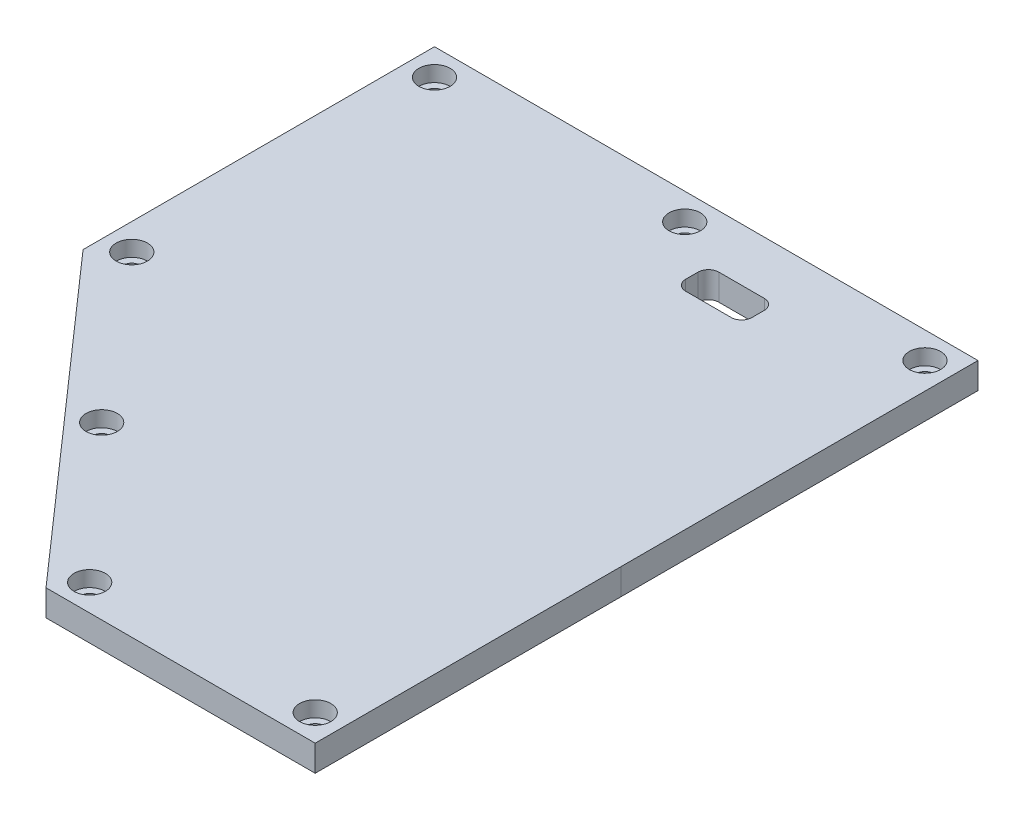
SolidWorks part; units mm, degrees
ref_plane "Front Plane" through (0, 0, 0) normal (0, 0, 1) x (1, 0, 0)
ref_plane "Top Plane" through (0, 0, 0) normal (0, 1, 0) x (1, 0, 0)
ref_plane "Right Plane" through (0, 0, 0) normal (1, 0, 0) x (0, 0, -1)
sketch "Sketch1" plane through (0, 0, 0) normal (0, 1, 0) x (1, 0, 0)
  line L0 (0, 0) -> (104.14, 0)
  line L2 (0, 0) -> (0, -67.34)
  line L4 (104.1401, -68.3797) -> (104.1401, -126.9997)
  line L5 (104.1401, -126.9997) -> (52.5601, -126.9997)
  line L6 (0, -67.34) -> (52.5601, -126.9997)
  line L11 (104.14, 0) -> (104.1401, -68.3797)
  dimension "D1" = 104.14
  dimension "D2" = 138.62
  dimension "D3" = 67.34
  dimension "D6" = 51.58
  dimension "D9" = 79.51
extrude "Boss-Extrude1" add sketch "Sketch1" along normal blind 5
sketch "Sketch2" plane through (0, 5, 0) normal (0, 1, 0) x (1, 0, 0)
  line L2 (104.1401, -126.9997) -> (104.1401, -68.3797) construction
  line L3 (52.5601, -126.9997) -> (104.1401, -126.9997) construction
  line L5 (104.14, 0) -> (0, 0) construction
  line L6 (0, 0) -> (0, -67.34) construction
  line L7 (0, -67.34) -> (52.5601, -126.9997) construction
  line L8 (104.1401, -68.3797) -> (104.14, 0) construction
  point P5 (99.0601, -121.9197)
  point P10 (55.8501, -121.9197)
  point P11 (99.06, -5.08)
  point P16 (5.08, -5.08)
  point P19 (53.03, -5.08)
  point P20 (5.08, -63.08)
  point P23 (30.4656, -94.2361)
  dimension "D2" = 5.08
  dimension "D3" = 5.08
  dimension "D4" = 5.08
  dimension "D5" = 43.21
  dimension "D6" = 5.08
  dimension "D8" = 5.08
  dimension "D9" = 5.08
  dimension "D10" = 5.08
  dimension "D11" = 47.95
  dimension "D12" = 58
  dimension "D13" = 5.08
  dimension "D14" = 37.56
  dimension "D15" = 5.08
hole_wizard "Ø4.0mm Dowel Hole1" positions "3DSketch1" profile "Sketch3" hole size "Ø4.0" standard "ANSI Metric"
sketch3d "3DSketch1"
  point P0 (5.08, 5, 5.08)
  point P3 (53.03, 5, 5.08)
  point P6 (99.06, 5, 5.08)
  point P12 (99.0601, 5, 121.9197)
  point P15 (55.8501, 5, 121.9197)
  point P18 (30.4656, 5, 94.2361)
  point P21 (5.08, 5, 63.08)
sketch "Sketch3" plane through (5.08, 5, 5.08) normal (1, 0, 0) x (0, 0, 1)
  line L0 (0, 0) -> (0, 5)
  line L1 (0, 5) -> (1.65, 5)
  line L2 (1.65, 5) -> (1.65, 0)
  line L5 (1.65, 0) -> (0, 0)
  line L10 (0, 5) -> (-1.65, 5) construction
  line L11 (0, -6.35) -> (0, 107.95) construction
  dimension "Hole Dia." = 3.3
  dimension "Hole Depth" = 5
  dimension "Drill Angle" = 180
sketch "Sketch4" plane through (0, 5, 0) normal (0, 1, 0) x (1, 0, 0)
  line L0 (104.14, 0) -> (0, 0) construction
  line L1 (0, 0) -> (0, -67.34) construction
  line L3 (62.65, -10.16) -> (75.35, -10.16)
  line L4 (62.65, -10.16) -> (62.65, -16.51)
  line L5 (62.65, -16.51) -> (75.35, -16.51)
  line L6 (75.35, -10.16) -> (75.35, -16.51)
  line L7 (62.65, -10.16) -> (75.35, -16.51) construction
  line L8 (62.65, -16.51) -> (75.35, -10.16) construction
  point P0 (69, -13.335)
  point P5 (69, -13.335)
  dimension "D1" = 13.335
  dimension "D2" = 69
  dimension "D3" = 6.35
  dimension "D4" = 12.7
extrude "Cut-Extrude1" cut sketch "Sketch4" against normal up to surface (5 mm away) up to face at (5.08, 0, 6.73)
fillet "Fillet1" radius 2 4 edges at (62.65, 2.5, 10.16) (75.35, 2.5, 10.16) (75.35, 2.5, 16.51) (62.65, 2.5, 16.51)
sketch "Sketch5" plane through (0, 5, 0) normal (0, 1, 0) x (1, 0, 0)
  circle A0 centre (55.8501, -121.9197) radius 3
  circle A1 centre (99.0601, -121.9197) radius 3
  circle A2 centre (30.4656, -94.2361) radius 3
  circle A3 centre (5.08, -63.08) radius 3
  circle A4 centre (5.08, -5.08) radius 3
  circle A5 centre (53.03, -5.08) radius 3
  circle A6 centre (99.06, -5.08) radius 3
extrude "Cut-Extrude2" cut sketch "Sketch5" against normal blind 3
